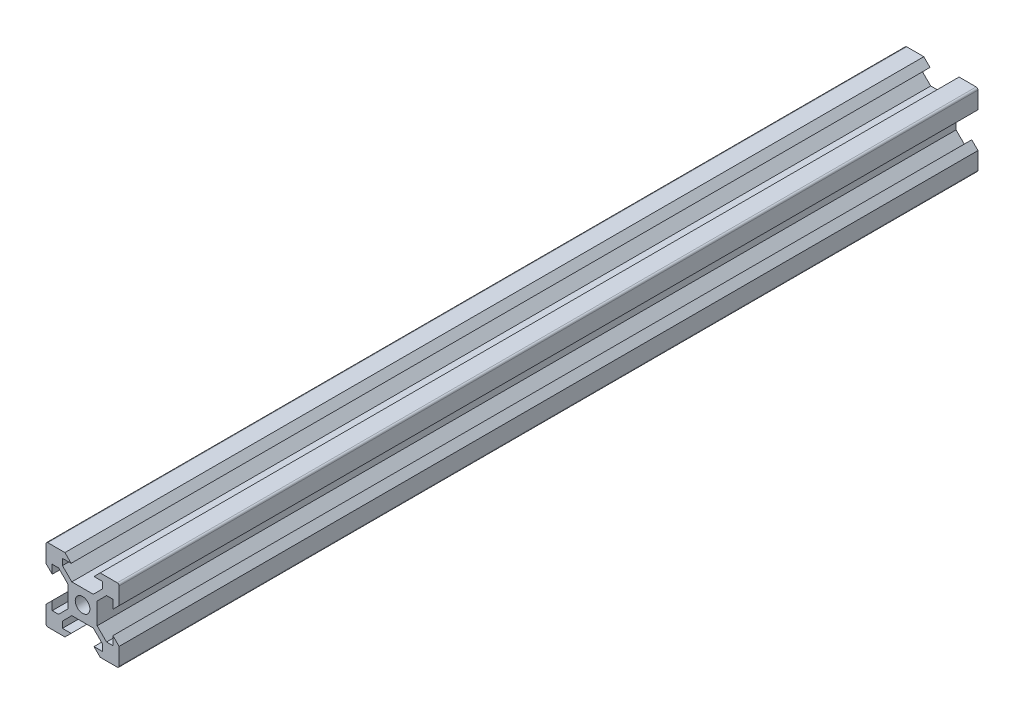
SolidWorks part; units mm, degrees
ref_plane "Alzado" through (0, 0, 0) normal (0, 0, 1) x (1, 0, 0)
ref_plane "Planta" through (0, 0, 0) normal (0, 1, 0) x (1, 0, 0)
ref_plane "Vista lateral" through (0, 0, 0) normal (1, 0, 0) x (0, 0, -1)
sketch "Croquis1" plane through (0, 0, 0) normal (0, 0, 1) x (1, 0, 0)
  line L0 (-4.825, 10) -> (-3.125, 8.3)
  line L1 (-9.5, -10) -> (-4.825, -10)
  line L2 (-10, -9.5) -> (-10, -4.825)
  line L3 (-9.5, 10) -> (-4.825, 10)
  line L4 (10, -9.5) -> (10, -4.825)
  line L5 (-10, -10) -> (10, 10) construction
  line L6 (-10, 10) -> (10, -10) construction
  line L7 (-2.9393, -4) -> (2.9393, -4)
  line L8 (-4, -2.9393) -> (-4, 2.9393)
  line L9 (-2.9393, 4) -> (2.9393, 4)
  line L10 (4, -2.9393) -> (4, 2.9393)
  line L11 (-4, -4) -> (4, 4) construction
  line L12 (-4, 4) -> (4, -4) construction
  line L13 (0, 10) -> (0, -10) construction
  line L14 (-3.125, 8.3) -> (-5.5, 8.3)
  line L15 (-6.5607, 5.5) -> (-4, 2.9393)
  line L16 (-5.5, 6.5607) -> (-2.9393, 4)
  line L17 (-9.4697, 10.5303) -> (10.5303, -9.4697) construction
  line L18 (-10, 4.825) -> (-8.3, 3.125)
  line L19 (-5.5, 8.3) -> (-5.5, 6.5607)
  line L20 (-8.3, 3.125) -> (-8.3, 5.5)
  line L21 (-8.3, 5.5) -> (-6.5607, 5.5)
  line L22 (10, 4.825) -> (8.3, 3.125)
  line L23 (8.3, 3.125) -> (8.3, 5.5)
  line L24 (8.3, 5.5) -> (6.5607, 5.5)
  line L25 (6.5607, 5.5) -> (4, 2.9393)
  line L26 (5.5, 6.5607) -> (2.9393, 4)
  line L27 (5.5, 8.3) -> (5.5, 6.5607)
  line L28 (3.125, 8.3) -> (5.5, 8.3)
  line L29 (4.825, 10) -> (3.125, 8.3)
  line L30 (4.825, -10) -> (3.125, -8.3)
  line L31 (3.125, -8.3) -> (5.5, -8.3)
  line L32 (5.5, -8.3) -> (5.5, -6.5607)
  line L33 (5.5, -6.5607) -> (2.9393, -4)
  line L34 (6.5607, -5.5) -> (4, -2.9393)
  line L35 (8.3, -5.5) -> (6.5607, -5.5)
  line L36 (8.3, -3.125) -> (8.3, -5.5)
  line L37 (10, -4.825) -> (8.3, -3.125)
  line L38 (-10, -4.825) -> (-8.3, -3.125)
  line L39 (-8.3, -3.125) -> (-8.3, -5.5)
  line L40 (-8.3, -5.5) -> (-6.5607, -5.5)
  line L41 (-6.5607, -5.5) -> (-4, -2.9393)
  line L42 (-5.5, -6.5607) -> (-2.9393, -4)
  line L43 (-5.5, -8.3) -> (-5.5, -6.5607)
  line L44 (-3.125, -8.3) -> (-5.5, -8.3)
  line L45 (-4.825, -10) -> (-3.125, -8.3)
  line L46 (-10, 4.825) -> (-10, 9.5)
  line L47 (4.825, 10) -> (9.5, 10)
  line L48 (10, 4.825) -> (10, 9.5)
  line L49 (4.825, -10) -> (9.5, -10)
  circle A0 centre (0, 0) radius 2
  arc A1 (-10, 9.5) -> (-9.5, 10) centre (-9.5, 9.5) cw
  arc A2 (9.5, 10) -> (10, 9.5) centre (9.5, 9.5) cw
  arc A3 (9.5, -10) -> (10, -9.5) centre (9.5, -9.5) ccw
  arc A4 (-9.5, -10) -> (-10, -9.5) centre (-9.5, -9.5) cw
  point P0 (0, 0)
  point P59 (0, 0)
  dimension "D2" = 4
  dimension "D9" = 0.5
  dimension "D1" = 20
  dimension "D3" = 8
  dimension "D4" = 3.125
  dimension "D5" = 5.5
  dimension "D6" = 4.3
  dimension "D7" = 4
  dimension "D8" = 0.75
extrude "Saliente-Extruir2" add sketch "Croquis1" along normal blind 100
other "Переместить грань1" face at (0, 0, 0) parameters "D1"=135
